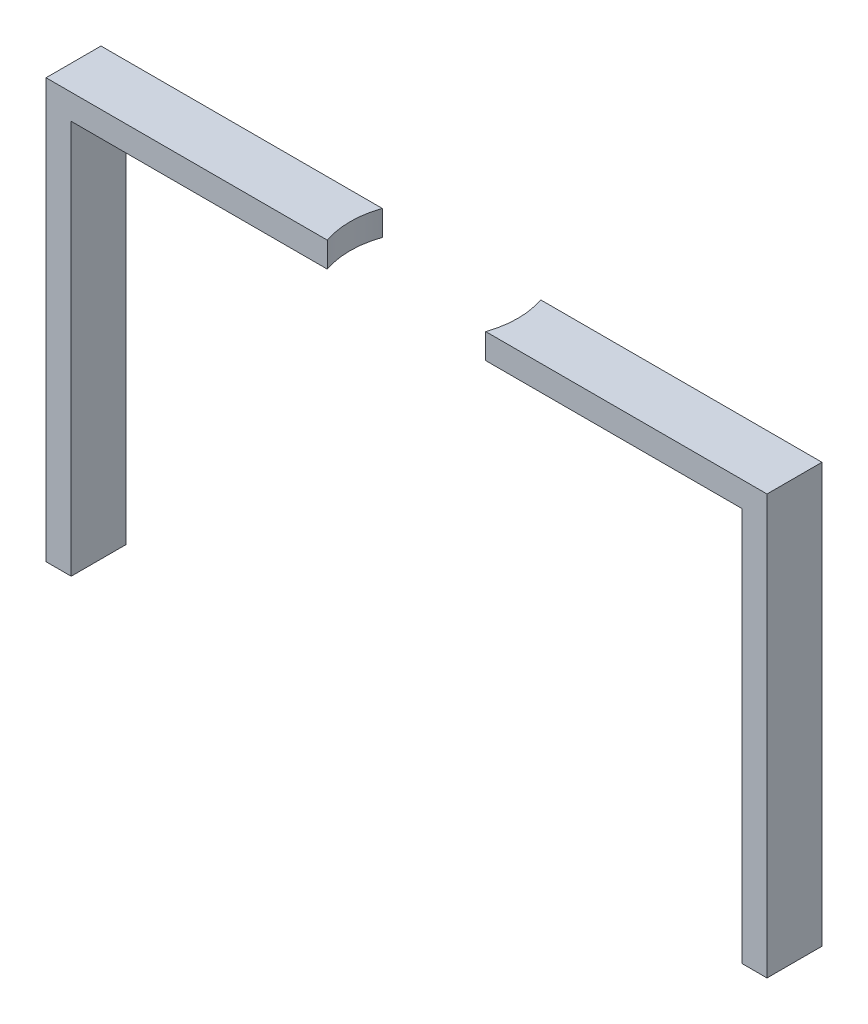
SolidWorks part; units mm, degrees
ref_plane "前视基准面" through (0, 0, 0) normal (0, 0, 1) x (1, 0, 0)
ref_plane "上视基准面" through (0, 0, 0) normal (0, 1, 0) x (1, 0, 0)
ref_plane "右视基准面" through (0, 0, 0) normal (1, 0, 0) x (0, 0, -1)
sketch "草图1" plane through (0, 0, 0) normal (0, 0, 1) x (1, 0, 0)
  line L0 (-369.8544, -113.9272) -> (-354.8544, -113.9272)
  line L1 (-354.8544, -113.9272) -> (-354.8544, 121.0728)
  line L2 (-354.8544, 121.0728) -> (45.1456, 121.0728)
  line L3 (45.1456, 121.0728) -> (45.1456, -113.9272)
  line L4 (45.1456, -113.9272) -> (60.1456, -113.9272)
  line L5 (60.1456, -113.9272) -> (60.1456, 136.0728)
  line L6 (60.1456, 136.0728) -> (-369.8544, 136.0728)
  line L7 (-369.8544, 136.0728) -> (-369.8544, -113.9272)
  dimension "D1" = 15
  dimension "D2" = 250
  dimension "D3" = 235
  dimension "D4" = 400
extrude "凸台-拉伸1" add sketch "草图1" along normal blind 32.78
sketch "草图2" plane through (0, 136.0728, 0) normal (0, 1, 0) x (1, 0, 0)
  line L1 (-154.8544, 0) -> (-154.8544, -32.78) construction
  line L2 (60.1456, 0) -> (-369.8544, 0) construction
  line L3 (60.1456, -32.78) -> (-369.8544, -32.78) construction
  line L4 (-154.8544, -32.78) -> (-154.8544, -16.39) construction
  line L5 (-369.8544, -16.39) -> (60.1456, -16.39) construction
  line L6 (-369.8544, -32.78) -> (-369.8544, 0) construction
  line L7 (60.1456, -32.78) -> (60.1456, 0) construction
  circle A0 centre (-154.8544, -16.39) radius 50
  point P14 (-154.8544, -16.39)
  dimension "D1" = 100
extrude "切除-拉伸1" cut sketch "草图2" against normal blind 15
